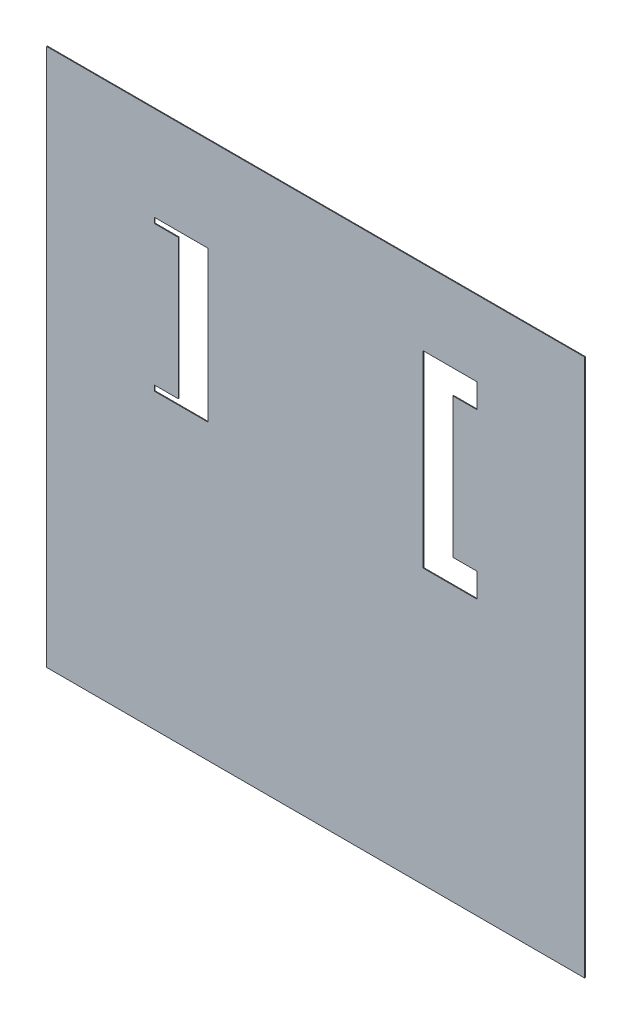
SolidWorks part; units mm, degrees
material "Copper"
ref_plane "Front Plane" through (0, 0, 0) normal (0, 0, 1) x (1, 0, 0)
ref_plane "Top Plane" through (0, 0, 0) normal (0, 1, 0) x (1, 0, 0)
ref_plane "Right Plane" through (0, 0, 0) normal (1, 0, 0) x (0, 0, -1)
sketch "Sketch1" plane through (0, 0, 0) normal (0, 0, 1) x (1, 0, 0)
  line L1 (0, 0) -> (25.4, 0)
  line L2 (0, 0) -> (0, 25.4)
  line L3 (0, 25.4) -> (25.4, 25.4)
  line L4 (25.4, 0) -> (25.4, 25.4)
  dimension "D1" = 25.4
  dimension "D2" = 25.4
extrude "Boss-Extrude1" add sketch "Sketch1" along normal blind 0.0356
sketch "Sketch2" plane through (0, 0, 0.0356) normal (0, 0, 1) x (1, 0, 0)
  line L0 (25.4, 25.4) -> (0, 25.4) construction
  line L1 (5.08, 20.955) -> (7.62, 20.955)
  line L2 (5.08, 20.955) -> (5.08, 20.701)
  line L3 (5.08, 13.843) -> (7.62, 13.843)
  line L4 (7.62, 20.955) -> (7.62, 13.843)
  line L5 (17.78, 21.844) -> (20.32, 21.844)
  line L6 (17.78, 21.844) -> (17.78, 12.954)
  line L7 (17.78, 12.954) -> (20.32, 12.954)
  line L8 (20.32, 21.844) -> (20.32, 20.701)
  line L9 (5.08, 14.097) -> (5.08, 13.843)
  line L10 (5.08, 14.097) -> (6.223, 14.097)
  line L11 (20.32, 14.097) -> (20.32, 12.954)
  line L12 (5.08, 20.701) -> (6.223, 20.701)
  line L13 (6.223, 14.097) -> (6.223, 20.701)
  line L14 (20.32, 14.097) -> (19.177, 14.097)
  line L16 (20.32, 20.701) -> (19.177, 20.701)
  line L17 (19.177, 14.097) -> (19.177, 20.701)
  point P10 (6.35, 20.955)
  point P11 (12.7, 25.4)
  point P12 (6.35, 13.843)
  point P13 (19.05, 12.954)
  point P22 (19.177, 17.399)
  point P23 (17.78, 17.399)
  point P24 (6.223, 17.399)
  point P25 (7.62, 17.399)
  dimension "D1" = 2.54
  dimension "D2" = 2.54
  dimension "D3" = 8.89
  dimension "D4" = 7.112
  dimension "D5" = 4.445
  dimension "D6" = 3.556
  dimension "D7" = 6.35
  dimension "D8" = 12.7
  dimension "D9" = 0
  dimension "D10" = 6.604
  dimension "D11" = 1.143
  dimension "D12" = 0
  dimension "D13" = 6.604
  dimension "D14" = 1.143
extrude "Cut-Extrude1" cut sketch "Sketch2" against normal through all
